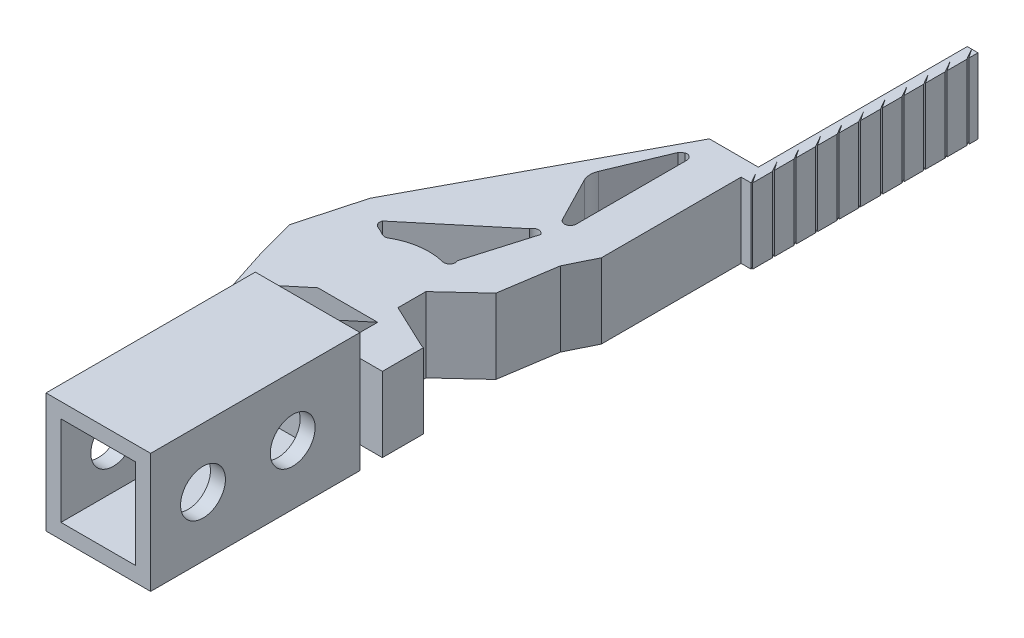
SolidWorks part; units mm, degrees
ref_plane "Alzado" through (0, 0, 0) normal (0, 0, 1) x (1, 0, 0)
ref_plane "Planta" through (0, 0, 0) normal (0, 1, 0) x (1, 0, 0)
ref_plane "Vista lateral" through (0, 0, 0) normal (1, 0, 0) x (0, 0, -1)
sketch "Croquis1" plane through (0, 0, 0) normal (0, 1, 0) x (1, 0, 0)
  line L0 (20.5589, -63.0871) -> (9.8211, -72.0432)
  line L1 (19.4443, -71.6177) -> (21.9723, -63.0315)
  line L2 (18.5918, -53.8135) -> (21.6723, -59.8084)
  line L3 (21.6465, -44.351) -> (18.5142, -51.8412)
  line L4 (23.1461, -59.4519) -> (23.1461, -44.652)
  line L5 (28.7233, -61.6595) -> (26.916, -65.3393)
  line L6 (25.7647, -72.8187) -> (26.916, -65.3393)
  line L7 (25.7647, -72.8187) -> (16.0443, -81.8064)
  line L9 (5.4331, -83.889) -> (4.0318, -78.6969)
  line L10 (6.3541, -70.2358) -> (4.0318, -78.6969)
  line L11 (6.3541, -70.2358) -> (22.1707, -40.6595)
  line L12 (28.7233, -40.6595) -> (28.7233, -61.6595)
  line L13 (22.1707, -40.6595) -> (28.7233, -40.6595)
  line L14 (14.2357, -96.6937) -> (20.2357, -96.6937) construction
  line L15 (26.916, -83.889) -> (27.2357, -83.9908)
  line L16 (7.2357, -89.4626) -> (5.4331, -83.889)
  line L17 (10.2357, -91.2626) -> (16.2357, -91.2626) construction
  line L18 (21.6465, -44.351) -> (22.1707, -43.8968)
  line L19 (20.9045, -81.051) -> (26.916, -83.889)
  line L21 (20.9045, -81.051) -> (20.9045, -77.3126)
  line L22 (17.2357, -89.4626) -> (17.2357, -84.3003) construction
  line L24 (7.2357, -89.4626) -> (27.2357, -89.4626)
  line L25 (27.2357, -83.9908) -> (27.2357, -89.4626)
  line L27 (17.2357, -96.6937) -> (17.2357, -94.2881) construction
  arc A0 (19.1647, -72.6351) -> (19.4443, -71.6177) centre (18.7505, -71.9742) ccw
  arc A1 (18.5601, -72.7306) -> (18.6272, -72.7444) centre (18.7505, -71.9742) ccw
  arc A2 (18.6272, -72.7444) -> (19.1647, -72.6351) centre (18.7505, -71.9742) ccw
  arc A3 (18.5601, -72.7306) -> (12.1757, -73.6205) centre (16.4657, -81.051) ccw
  arc A4 (11.7857, -73.725) -> (12.1757, -73.6205) centre (11.7857, -72.945) ccw
  arc A5 (11.3957, -73.6205) -> (11.7857, -73.725) centre (11.7857, -72.945) ccw
  arc A6 (11.3957, -73.6205) -> (10.2544, -73.0697) centre (7.1057, -81.051) ccw
  arc A7 (9.8397, -72.6861) -> (10.2544, -73.0697) centre (10.5407, -72.3441) ccw
  arc A8 (9.8211, -72.0432) -> (9.8397, -72.6861) centre (10.5407, -72.3441) ccw
  arc A9 (21.9723, -63.0315) -> (21.0831, -62.6329) centre (21.2785, -63.388) ccw
  arc A10 (21.0831, -62.6329) -> (20.5589, -63.0871) centre (21.2785, -63.388) ccw
  arc A11 (22.8377, -60.0732) -> (23.1461, -59.4519) centre (22.3661, -59.4519) ccw
  arc A12 (21.6723, -59.8084) -> (22.8377, -60.0732) centre (22.3661, -59.4519) ccw
  arc A13 (18.4527, -53.4827) -> (18.5918, -53.8135) centre (20.6731, -52.744) ccw
  arc A14 (18.5142, -51.8412) -> (18.4527, -53.4827) centre (20.6731, -52.744) ccw
  arc A15 (23.1461, -44.652) -> (22.8377, -44.0307) centre (22.3661, -44.652) ccw
  arc A16 (22.8377, -44.0307) -> (22.1707, -43.8968) centre (22.3661, -44.652) ccw
  point P9 (0, 0)
  point P17 (22.1707, -40.6595)
  point P50 (0, 0)
  point P54 (4.4242, -77.0466)
  point P55 (0.4443, -77.0466)
  point P56 (5.4331, -83.889)
  point P59 (4.0318, -78.6969)
  point P60 (4.4802, -74.3807)
  point P63 (10.5407, -61.6595)
  point P66 (6.3541, -70.2358)
  point P67 (20.9045, -81.051)
  dimension "D1" = 20
extrude "Saliente-Extruir1" add sketch "Croquis1" along normal mid plane 10
sketch "Croquis2" plane through (0, -5, 0) normal (0, -1, 0) x (1, 0, 0)
  line L0 (30.167, 42.9692) -> (28.7233, 42.9692)
  line L1 (28.7233, 42.9692) -> (28.7233, 12.7212)
  line L2 (28.7233, 12.7212) -> (30.167, 12.7212)
  line L3 (30.167, 12.7212) -> (30.167, 42.9692)
  line L4 (28.7233, 40.6595) -> (28.7233, 61.6595) construction
extrude "Saliente-Extruir2" add sketch "Croquis2" against normal up to vertex (10 mm away)
sketch "Sketch2" plane through (0, 5, 0) normal (0, 1, 0) x (1, 0, 0)
  line L0 (30.167, -13.9574) -> (29.3175, -12.7212)
  line L1 (29.3175, -12.7212) -> (30.167, -14.2212)
  line L2 (30.167, -12.7212) -> (30.167, -42.9692) construction
  line L3 (30.167, -13.9574) -> (30.167, -14.2212)
  line L4 (28.7233, -12.7212) -> (30.167, -12.7212) construction
  line L5 (30.167, -16.8482) -> (30.167, -17.112)
  line L6 (29.3175, -15.612) -> (30.167, -17.112)
  line L7 (30.167, -16.8482) -> (29.3175, -15.612)
  line L8 (29.3175, -18.5029) -> (30.167, -20.0029)
  line L9 (30.167, -19.7391) -> (29.3175, -18.5029)
  line L10 (29.3175, -21.3937) -> (30.167, -22.8937)
  line L11 (30.167, -22.6299) -> (29.3175, -21.3937)
  line L12 (29.3175, -24.2845) -> (30.167, -25.7845)
  line L13 (30.167, -25.5207) -> (29.3175, -24.2845)
  line L14 (29.3175, -27.1753) -> (30.167, -28.6753)
  line L15 (30.167, -28.4115) -> (29.3175, -27.1753)
  line L16 (29.3175, -30.0662) -> (30.167, -31.5662)
  line L17 (30.167, -31.3024) -> (29.3175, -30.0662)
  line L18 (29.3175, -32.957) -> (30.167, -34.457)
  line L19 (30.167, -34.1932) -> (29.3175, -32.957)
  line L20 (29.3175, -35.8478) -> (30.167, -37.3478)
  line L21 (30.167, -37.084) -> (29.3175, -35.8478)
  line L22 (29.3175, -38.7386) -> (30.167, -40.2386)
  line L23 (30.167, -39.9748) -> (29.3175, -38.7386)
  line L24 (29.3175, -41.6295) -> (30.167, -43.1295)
  line L25 (30.167, -42.8657) -> (29.3175, -41.6295)
  line L26 (29.3175, -44.5203) -> (30.167, -46.0203)
  line L27 (30.167, -45.7565) -> (29.3175, -44.5203)
  line L28 (29.3175, -47.4111) -> (30.167, -48.9111)
  line L29 (30.167, -48.6473) -> (29.3175, -47.4111)
  line L30 (29.3175, -50.3019) -> (30.167, -51.8019)
  line L31 (30.167, -51.5381) -> (29.3175, -50.3019)
  line L32 (29.3175, -53.1927) -> (30.167, -54.6927)
  line L33 (30.167, -54.429) -> (29.3175, -53.1927)
  line L34 (30.167, -19.7391) -> (30.167, -20.0029)
  line L35 (30.167, -22.6299) -> (30.167, -22.8937)
  line L36 (30.167, -25.5207) -> (30.167, -25.7845)
  line L37 (30.167, -28.4115) -> (30.167, -28.6753)
  line L38 (30.167, -31.3024) -> (30.167, -31.5662)
  line L39 (30.167, -34.1932) -> (30.167, -34.457)
  line L40 (30.167, -37.084) -> (30.167, -37.3478)
  line L41 (30.167, -39.9748) -> (30.167, -40.2386)
  line L42 (30.167, -42.8657) -> (30.167, -43.1295)
  line L43 (30.167, -45.7565) -> (30.167, -46.0203)
  line L44 (30.167, -48.6473) -> (30.167, -48.9111)
  line L45 (30.167, -51.5381) -> (30.167, -51.8019)
  line L46 (30.167, -54.429) -> (30.167, -54.6927)
  dimension "D1" = 1.5
  dimension "D2" = 1.5
  dimension "D3" = 15
extrude "Cut-Extrude1" cut sketch "Sketch2" against normal through all contours L0 L1 L3 | L5 L6 L7 | L9 L8 L34 | L11 L10 L35 | L13 L12 L36 | L15 L14 L37 | L17 L16 L38 | L19 L18 L39 | L21 L20 L40 | L23 L22 L41 | L25 L24 L42 | L27 L26 L43 | L29 L28 L44 | L31 L30 L45 | L33 L32 L46
sketch "Sketch7" plane through (0, 0, 89.4626) normal (0, 0, 1) x (1, 0, 0)
  line L0 (17.2357, 8) -> (17.2357, -13.6231) construction
  line L1 (10.2357, 8) -> (10.2357, -8)
  line L2 (10.2357, -8) -> (24.2357, -8)
  line L4 (24.2357, 8) -> (24.2357, -8)
  line L5 (17.2357, 5) -> (17.2357, -26.4269) construction
  line L6 (7.2357, 5) -> (27.2357, 5) construction
  line L7 (27.2357, 0) -> (-22.3956, 0) construction
  line L12 (10.2357, 8) -> (24.2357, 8)
  line L14 (10.2357, -8) -> (24.2357, 8) construction
  line L15 (10.2357, 8) -> (24.2357, -8) construction
  line L16 (27.2357, 5) -> (27.2357, -5) construction
  point P6 (17.2357, 0)
  dimension "D3" = 16
  dimension "D1" = 14
extrude "Boss-Extrude2" add sketch "Sketch7" along normal blind 28 contours L4 L2 L1 L12
sketch "Sketch8" plane through (10.2357, 0, 0) normal (-1, 0, 0) x (0, 0, 1)
  line L3 (89.4626, -12.9132) -> (89.4626, 7.1498)
  line L6 (111.4795, 0) -> (96.1954, 0) construction
  line L7 (90.62, 0) -> (117.4626, 0) construction
  line L8 (89.4626, 5) -> (89.4626, -5) construction
  line L9 (117.4626, 8) -> (117.4626, -8) construction
  line L10 (103.4626, 8) -> (103.4626, -8) construction
  line L11 (117.4626, 8) -> (89.4626, 8) construction
  line L12 (117.4626, -8) -> (89.4626, -8) construction
  circle A6 centre (110.4626, 0) radius 3
  circle A7 centre (110.4626, 0) radius 3
  circle A9 centre (98.4626, 0) radius 3
  circle A10 centre (98.4626, 0) radius 3
  point P0 (103.4626, 0)
  dimension "D3" = 0.5
  dimension "D4" = 0.5
sketch "Sketch9" plane through (0, 0, 117.4626) normal (0, 0, 1) x (1, 0, 0)
  line L0 (17.2357, 8) -> (17.2357, -16.0657) construction
  line L1 (10.2357, 8) -> (24.2357, 8) construction
  line L2 (10.2357, 0) -> (24.0173, 0) construction
  line L3 (10.2357, 8) -> (10.2357, -8) construction
  line L5 (12.2357, -6) -> (22.2357, -6)
  line L6 (12.2357, -6) -> (12.2357, 6)
  line L7 (12.2357, 6) -> (22.2357, 6)
  line L8 (22.2357, -6) -> (22.2357, 6)
  line L9 (12.2357, -6) -> (22.2357, 6) construction
  line L10 (12.2357, 6) -> (22.2357, -6) construction
  point P9 (17.2357, 0)
  dimension "D1" = 10
  dimension "D2" = 12
extrude "Cut-Extrude5" cut sketch "Sketch9" against normal blind 25.5 contours L6 L5 L8 L7
ref_plane "Plane1" through (17.2357, 0, 0) normal (1, 0, 0) x (0, 0, -1)
sketch "Sketch10" plane through (17.2357, 0, 0) normal (1, 0, 0) x (0, 0, -1)
  line L0 (-84.0979, 5) -> (-89.4626, 5)
  line L1 (-89.4626, -5) -> (-84.0979, -5)
  line L2 (-89.4626, 5) -> (-89.4626, 7.9257)
  line L3 (-89.4626, 7.9257) -> (-84.0979, 5)
  line L4 (-117.4626, 0) -> (128.384, 0) construction
  line L5 (-117.4626, 8) -> (-117.4626, -8) construction
  line L8 (-89.4626, -5) -> (-89.4626, -7.9257)
  line L9 (-89.4626, -7.9257) -> (-84.0979, -5)
ref_plane "Plano2" through (0, 20, 0) normal (0, -1, 0) x (-1, 0, 0)
ref_plane "Plano3" through (0, 12, 0) normal (0, -1, 0) x (-1, 0, 0)
ref_plane "Plano4" through (0, 28, 0) normal (0, -1, 0) x (-1, 0, 0)
extrude "Boss-Extrude4" add sketch "Sketch10" along normal mid plane 8
extrude "Cut-Extrude6" cut sketch "Sketch8" against normal blind 30 contours A10 | A7
